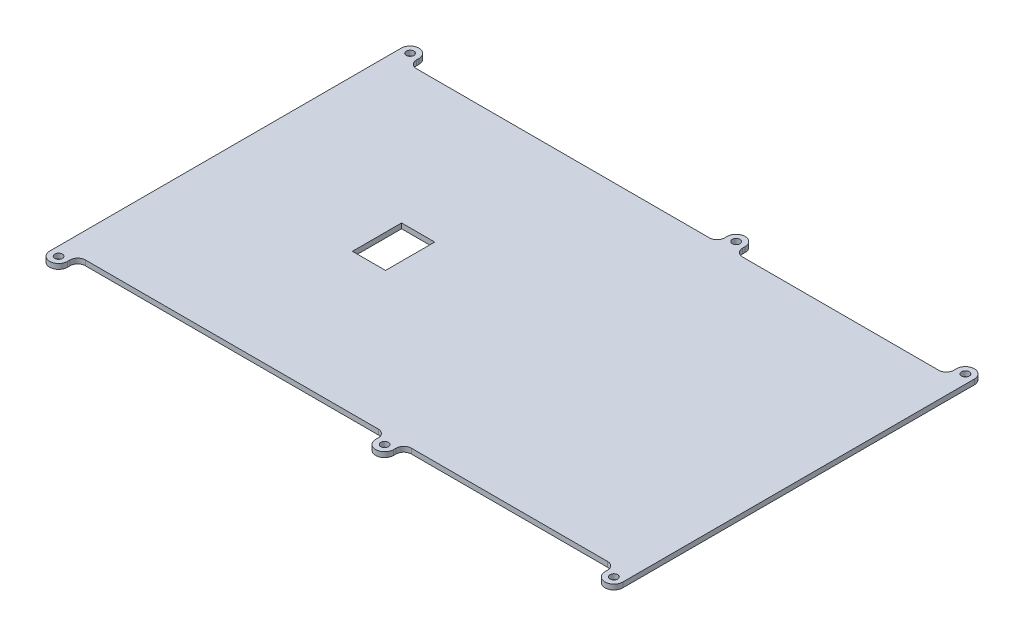
SolidWorks part; units mm, degrees
ref_plane "Front Plane" through (0, 0, 0) normal (0, 0, 1) x (1, 0, 0)
ref_plane "Top Plane" through (0, 0, 0) normal (0, 1, 0) x (1, 0, 0)
ref_plane "Right Plane" through (0, 0, 0) normal (1, 0, 0) x (0, 0, -1)
sketch "Sketch1" plane through (0, 0, 0) normal (0, 1, 0) x (1, 0, 0)
  line L0 (0, 118.7475) -> (0, -97.3161) construction
  line L1 (-222.6243, 0) -> (188.0716, 0) construction
  line L2 (-105.5, 65) -> (-105.5, 69)
  line L4 (-112.5, 65) -> (-112.5, -65)
  line L6 (112.5, 65) -> (112.5, -65)
  line L7 (-112.5, 65) -> (-112.5, 69)
  line L9 (112.5, 65) -> (112.5, 69)
  line L10 (105.5, 65) -> (105.5, 69)
  line L12 (22.5, 65) -> (22.5, 69)
  line L13 (15.5, 65) -> (15.5, 69)
  line L15 (-105.5, 65) -> (15.5, 65)
  line L16 (22.5, 65) -> (105.5, 65)
  line L17 (22.5, -65) -> (105.5, -65)
  line L18 (-105.5, -65) -> (15.5, -65)
  line L19 (15.5, -65) -> (15.5, -69)
  line L20 (22.5, -65) -> (22.5, -69)
  line L21 (105.5, -65) -> (105.5, -69)
  line L22 (112.5, -65) -> (112.5, -69)
  line L23 (-112.5, -65) -> (-112.5, -69)
  line L24 (-105.5, -65) -> (-105.5, -69)
  line L30 (-53, 9.65) -> (-40, 9.65)
  line L31 (-53, 9.65) -> (-53, -9.65)
  line L32 (-53, -9.65) -> (-40, -9.65)
  line L33 (-40, 9.65) -> (-40, -9.65)
  arc A2 (-105.5, 69) -> (-112.5, 69) centre (-109, 69) ccw
  circle A3 centre (-109, 69) radius 1.5
  circle A4 centre (109, 69) radius 1.5
  arc A5 (105.5, 69) -> (112.5, 69) centre (109, 69) cw
  arc A6 (22.5, 69) -> (15.5, 69) centre (19, 69) ccw
  circle A7 centre (19, 69) radius 1.5
  circle A8 centre (19, -69) radius 1.5
  arc A9 (22.5, -69) -> (15.5, -69) centre (19, -69) cw
  arc A10 (105.5, -69) -> (112.5, -69) centre (109, -69) ccw
  circle A11 centre (109, -69) radius 1.5
  circle A12 centre (-109, -69) radius 1.5
  arc A13 (-105.5, -69) -> (-112.5, -69) centre (-109, -69) cw
  point P10 (-112.5, 0)
  point P46 (-53, 0)
  dimension "D5" = 4
  dimension "D4" = 7
  dimension "D8" = 3
  dimension "D9" = 13
  dimension "D10" = 19.3
  dimension "D11" = 90
  dimension "D2" = 130
  dimension "D3" = 7
  dimension "D6" = 112.5
  dimension "D7" = 2
  dimension "D12" = 40
extrude "Boss-Extrude1" add sketch "Sketch1" along normal mid plane 2
fillet "Fillet1" radius 3 8 edges at (-105.5, 0, 65) (15.5, 0, 65) (22.5, 0, 65) (105.5, 0, 65) (105.5, 0, -65) (15.5, 0, -65) (22.5, 0, -65) (-105.5, 0, -65)
